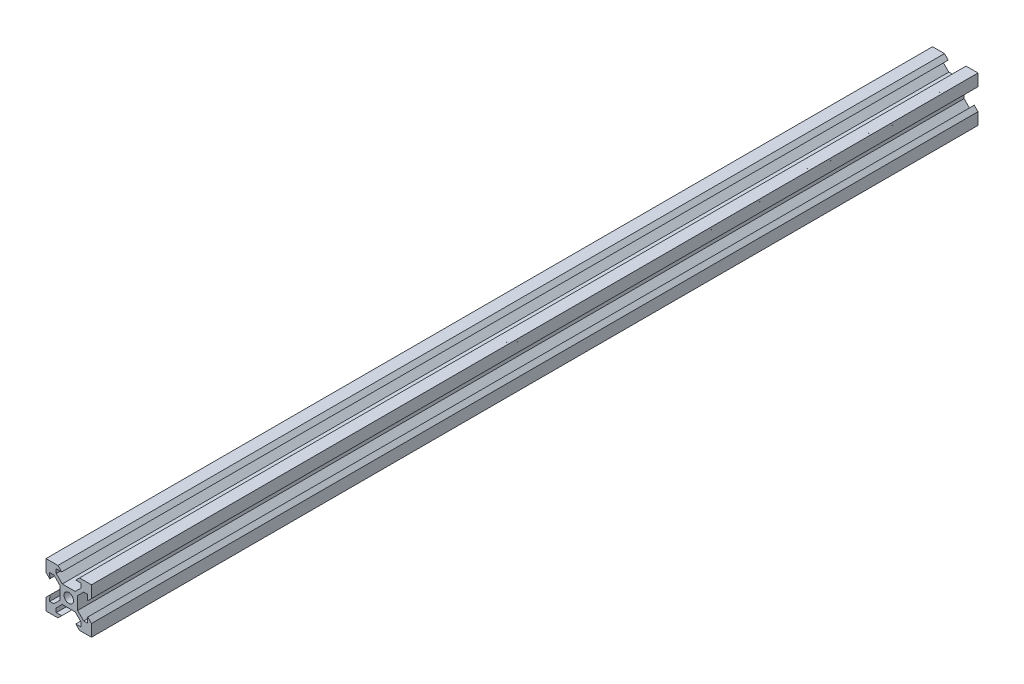
SolidWorks part; units mm, degrees
material "6061-T6 (SS)"
ref_plane "Front Plane" through (0, 0, 0) normal (0, 0, 1) x (1, 0, 0)
ref_plane "Top Plane" through (0, 0, 0) normal (0, 1, 0) x (1, 0, 0)
ref_plane "Right Plane" through (0, 0, 0) normal (1, 0, 0) x (0, 0, -1)
sketch "Sketch1" plane through (0, 0, 0) normal (0, 0, 1) x (1, 0, 0)
  line L0 (2.8343, 3.894) -> (5.5, 6.5588)
  line L1 (2.8343, -3.894) -> (-2.8343, -3.894)
  line L2 (3.8948, -2.8332) -> (3.8948, 2.8332)
  line L3 (2.8343, 3.894) -> (-2.8343, 3.894)
  line L4 (-3.8948, -2.8332) -> (-3.8948, 2.8332)
  line L5 (3.8994, -3.9006) -> (-3.8994, 3.9006) construction
  line L6 (3.9006, 3.8994) -> (-3.9006, -3.8994) construction
  line L7 (10, 4.747) -> (10, 9.9986)
  line L8 (5.5, 6.5588) -> (5.5, 8.3491)
  line L9 (5.5, 8.3491) -> (3.1, 8.3491)
  line L10 (3.1, 8.3491) -> (4.75, 9.9986)
  line L11 (4.75, 9.9986) -> (10, 9.9986)
  line L12 (8.35, 3.0975) -> (10, 4.747)
  line L13 (8.3507, 5.4975) -> (8.35, 3.0975)
  line L14 (6.5605, 5.498) -> (8.3507, 5.4975)
  line L15 (3.8948, 2.8332) -> (6.5605, 5.498)
  line L16 (0, -55) -> (0, 55) construction
  line L17 (-3.8948, 2.8332) -> (-6.5605, 5.498)
  line L18 (-6.5605, 5.498) -> (-8.3507, 5.4975)
  line L19 (-8.3507, 5.4975) -> (-8.35, 3.0975)
  line L20 (-8.35, 3.0975) -> (-10, 4.747)
  line L21 (-4.75, 9.9986) -> (-10, 9.9986)
  line L22 (-3.1, 8.3491) -> (-4.75, 9.9986)
  line L23 (-5.5, 8.3491) -> (-3.1, 8.3491)
  line L24 (-5.5, 6.5588) -> (-5.5, 8.3491)
  line L25 (-10, 4.747) -> (-10, 9.9986)
  line L26 (-2.8343, 3.894) -> (-5.5, 6.5588)
  line L27 (55, 0) -> (-55, 0) construction
  line L28 (3.8948, -2.8332) -> (6.5605, -5.498)
  line L29 (2.8343, -3.894) -> (5.5, -6.5588)
  line L30 (-3.8948, -2.8332) -> (-6.5605, -5.498)
  line L31 (-2.8343, -3.894) -> (-5.5, -6.5588)
  line L32 (-8.3507, -5.4975) -> (-8.35, -3.0975)
  line L33 (-8.35, -3.0975) -> (-10, -4.747)
  line L34 (8.3507, -5.4975) -> (8.35, -3.0975)
  line L35 (8.35, -3.0975) -> (10, -4.747)
  line L36 (-10, -4.747) -> (-10, -9.9986)
  line L37 (-5.5, -6.5588) -> (-5.5, -8.3491)
  line L38 (-5.5, -8.3491) -> (-3.1, -8.3491)
  line L39 (-3.1, -8.3491) -> (-4.75, -9.9986)
  line L40 (-4.75, -9.9986) -> (-10, -9.9986)
  line L41 (-6.5605, -5.498) -> (-8.3507, -5.4975)
  line L42 (6.5605, -5.498) -> (8.3507, -5.4975)
  line L43 (4.75, -9.9986) -> (10, -9.9986)
  line L44 (3.1, -8.3491) -> (4.75, -9.9986)
  line L45 (5.5, -8.3491) -> (3.1, -8.3491)
  line L46 (5.5, -6.5588) -> (5.5, -8.3491)
  line L47 (10, -4.747) -> (10, -9.9986)
  circle A0 centre (0, 0) radius 2.1
  point P0 (0, 0)
  dimension "D6" = 4.2
  dimension "D1" = 7.8
  dimension "D2" = 20
  dimension "D3" = 11
  dimension "D4" = 9.5
  dimension "D5" = 6.2
  dimension "D7" = 1.5
extrude "Boss-Extrude1" add sketch "Sketch1" along normal mid plane 390
